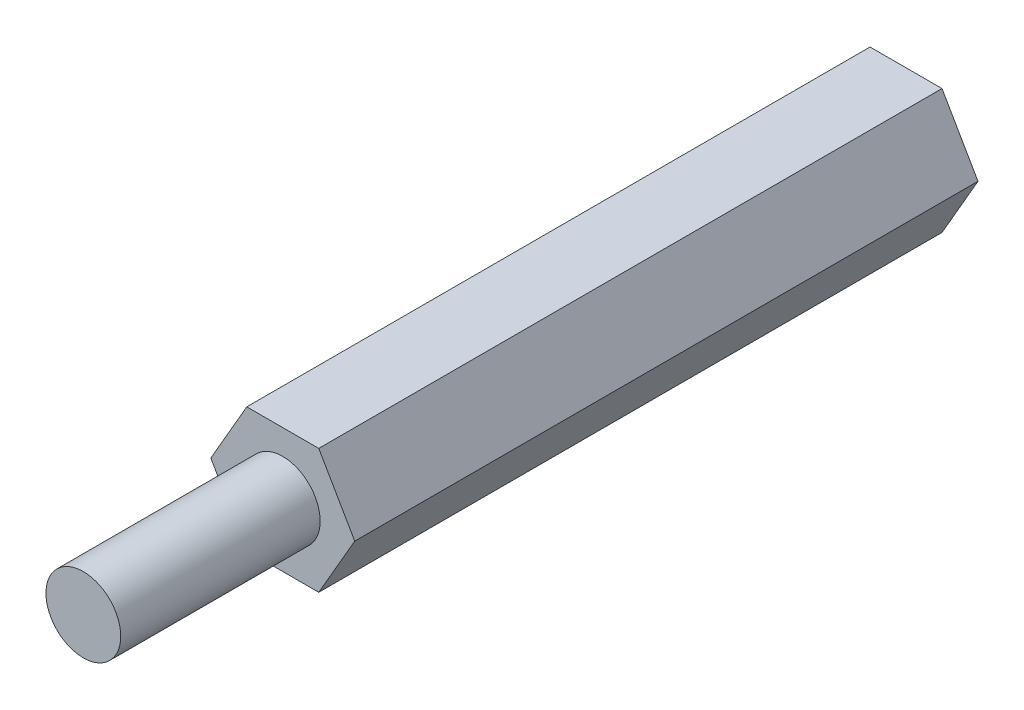
SolidWorks part; units mm, degrees
ref_plane "Plan de face" through (0, 0, 0) normal (0, 0, 1) x (1, 0, 0)
ref_plane "Plan de dessus" through (0, 0, 0) normal (0, 1, 0) x (1, 0, 0)
ref_plane "Plan de droite" through (0, 0, 0) normal (1, 0, 0) x (0, 0, -1)
sketch "Esquisse1" plane through (0, 0, 0) normal (0, 0, 1) x (1, 0, 0)
  line L1 (2.8868, 0) -> (1.4434, 2.5)
  line L2 (1.4434, 2.5) -> (-1.4434, 2.5)
  line L3 (-1.4434, 2.5) -> (-2.8868, 0)
  line L4 (-2.8868, 0) -> (-1.4434, -2.5)
  line L5 (-1.4434, -2.5) -> (1.4434, -2.5)
  line L6 (1.4434, -2.5) -> (2.8868, 0)
  circle A0 centre (0, 0) radius 2.5 construction
  dimension "D1" = 5
extrude "Boss.-Extru.1" add sketch "Esquisse1" along normal blind 25
sketch "Esquisse2" plane through (0, 0, 25) normal (0, 0, 1) x (1, 0, 0)
  circle A0 centre (0, 0) radius 1.5
  dimension "D1" = 3
extrude "Boss.-Extru.2" add sketch "Esquisse2" along normal blind 8
sketch "Esquisse3" plane through (0, 0, 0) normal (0, 0, -1) x (-1, 0, 0)
  circle A0 centre (0, 0) radius 1.5
  dimension "D1" = 3
extrude "Enlèv. mat.-Extru.1" cut sketch "Esquisse3" against normal blind 8
